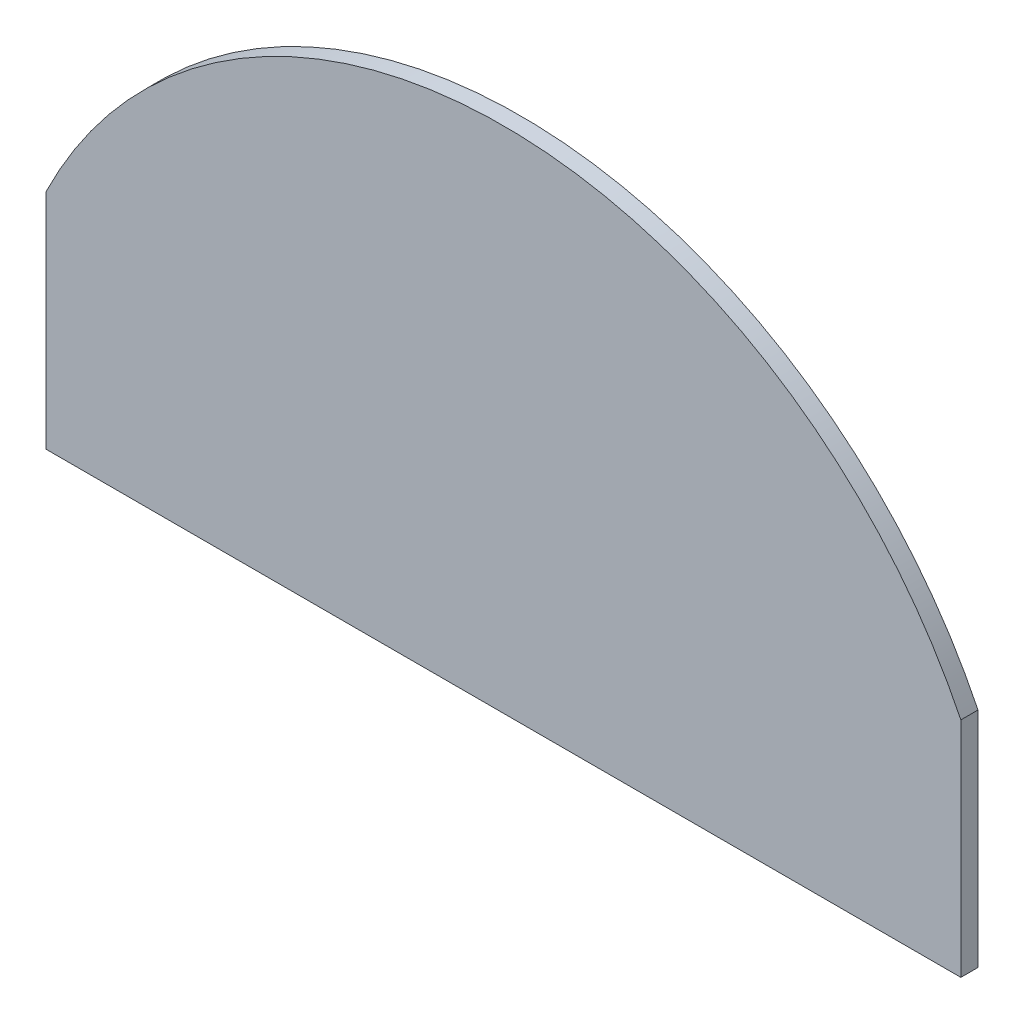
SolidWorks part; units mm, degrees
ref_plane "Front Plane" through (0, 0, 0) normal (0, 0, 1) x (1, 0, 0)
ref_plane "Top Plane" through (0, 0, 0) normal (0, 1, 0) x (1, 0, 0)
ref_plane "Right Plane" through (0, 0, 0) normal (1, 0, 0) x (0, 0, -1)
sketch "Sketch1" plane through (0, 0, 0) normal (0, 0, 1) x (1, 0, 0)
  line L0 (160, 0) -> (160, -39)
  line L1 (0, 0) -> (0, -39)
  line L2 (0, -39) -> (160, -39)
  arc A0 (0, 0) -> (160, 0) centre (80, -39) cw
  point P3 (80, 50)
  dimension "D1" = 50
  dimension "D2" = 39
  dimension "D3" = 39
  dimension "D4" = 160
extrude "Boss-Extrude1" add sketch "Sketch1" along normal blind 3 contours L2 L0 A0 L1
